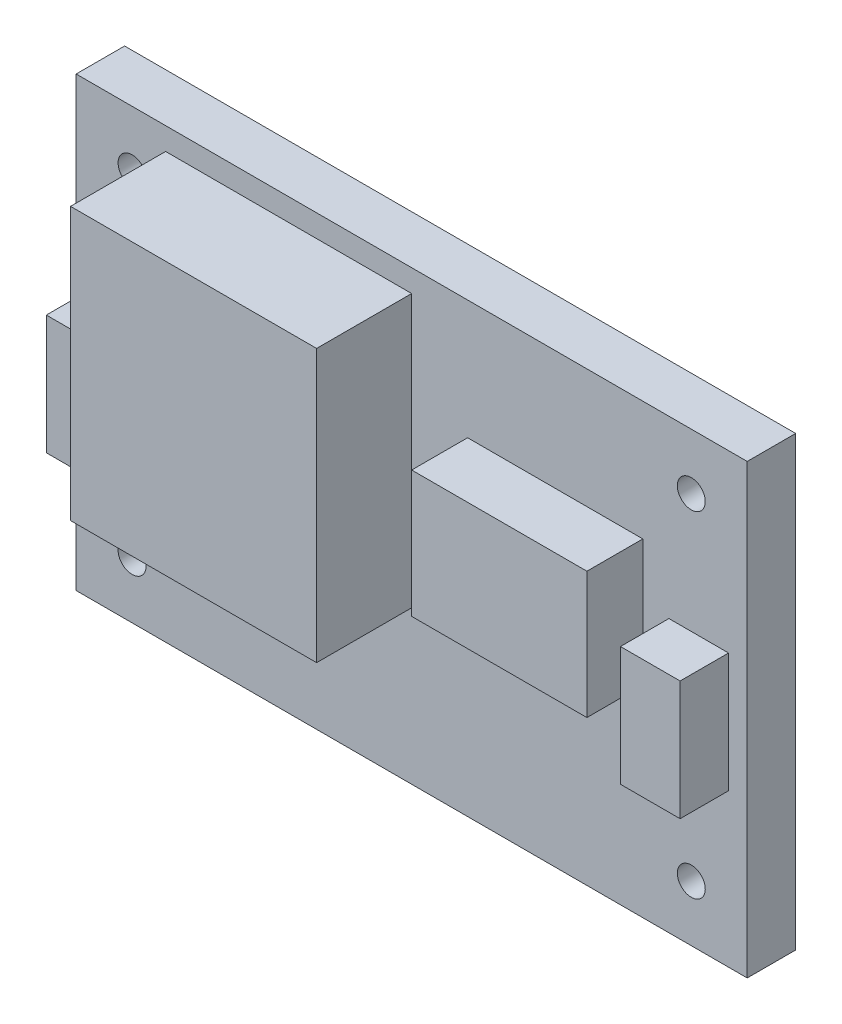
SolidWorks part; units mm, degrees
ref_plane "Ebene vorne" through (0, 0, 0) normal (0, 0, 1) x (1, 0, 0)
ref_plane "Ebene oben" through (0, 0, 0) normal (0, 1, 0) x (1, 0, 0)
ref_plane "Ebene rechts" through (0, 0, 0) normal (1, 0, 0) x (0, 0, -1)
sketch "Skizze1" plane through (0, 0, 0) normal (0, 0, 1) x (1, 0, 0)
  line L1 (0, 0) -> (18, 0)
  line L2 (0, 0) -> (0, 12)
  line L3 (0, 12) -> (18, 12)
  line L4 (18, 0) -> (18, 12)
  dimension "D1" = 18
  dimension "D2" = 12
extrude "Platine" add sketch "Skizze1" along normal blind 1.3
sketch "Skizze2" plane through (0, 0, 1.3) normal (0, 0, 1) x (1, 0, 0)
  line L0 (0, 12) -> (0, 0) construction
  line L1 (2.4, 11.4) -> (9, 11.4)
  line L2 (2.4, 11.4) -> (2.4, 4.1)
  line L3 (2.4, 4.1) -> (9, 4.1)
  line L4 (9, 11.4) -> (9, 4.1)
  line L5 (18, 12) -> (0, 12) construction
  dimension "D1" = 6.6
  dimension "D2" = 7.3
  dimension "D3" = 2.4
  dimension "D4" = 0.6
extrude "Aufsatz-Linear austragen2" add sketch "Skizze2" along normal blind 2.55
sketch "Skizze3" plane through (0, 0, 1.3) normal (0, 0, 1) x (1, 0, 0)
  line L0 (18, 0) -> (18, 12) construction
  line L1 (10.5, 8.8) -> (15.2, 8.8)
  line L2 (10.5, 8.8) -> (10.5, 5.4)
  line L3 (10.5, 5.4) -> (15.2, 5.4)
  line L4 (15.2, 8.8) -> (15.2, 5.4)
  line L5 (18, 12) -> (0, 12) construction
  dimension "D1" = 3.4
  dimension "D2" = 4.7
  dimension "D3" = 2.8
  dimension "D4" = 3.2
extrude "Aufsatz-Linear austragen3" add sketch "Skizze3" along normal blind 1.5
sketch "Skizze4" plane through (0, 0, 1.3) normal (0, 0, 1) x (1, 0, 0)
  line L0 (9, 12) -> (9, 6) construction
  line L1 (18, 12) -> (0, 12) construction
  line L2 (9, 4.1) -> (9, 11.4) construction
  line L3 (9, 6) -> (18, 6) construction
  line L4 (18, 0) -> (18, 12) construction
  circle A0 centre (1.5, 10.5) radius 0.375
  circle A1 centre (16.5, 10.5) radius 0.375
  circle A2 centre (16.5, 1.5) radius 0.375
  circle A3 centre (1.5, 1.5) radius 0.375
  dimension "D1" = 0.75
  dimension "D2" = 15
  dimension "D3" = 9
extrude "Schnitt-Linear austragen1" cut sketch "Skizze4" against normal through all
sketch "Skizze5" plane through (0, 0, 1.3) normal (0, 0, 1) x (1, 0, 0)
  line L0 (2.4, 4.1) -> (9, 4.1) construction
  line L1 (0.5, 7.3) -> (2.1, 7.3)
  line L2 (0.5, 7.3) -> (0.5, 4.1)
  line L3 (0.5, 4.1) -> (2.1, 4.1)
  line L4 (2.1, 7.3) -> (2.1, 4.1)
  line L5 (15.9, 7.3) -> (17.5, 7.3)
  line L6 (15.9, 7.3) -> (15.9, 4.1)
  line L7 (15.9, 4.1) -> (17.5, 4.1)
  line L8 (17.5, 7.3) -> (17.5, 4.1)
  line L9 (0, 12) -> (0, 0) construction
  line L10 (18, 0) -> (18, 12) construction
  dimension "D1" = 3.2
  dimension "D2" = 1.6
  dimension "D3" = 0.5
  dimension "D4" = 0.5
extrude "Aufsatz-Linear austragen4" add sketch "Skizze5" along normal blind 1.3
